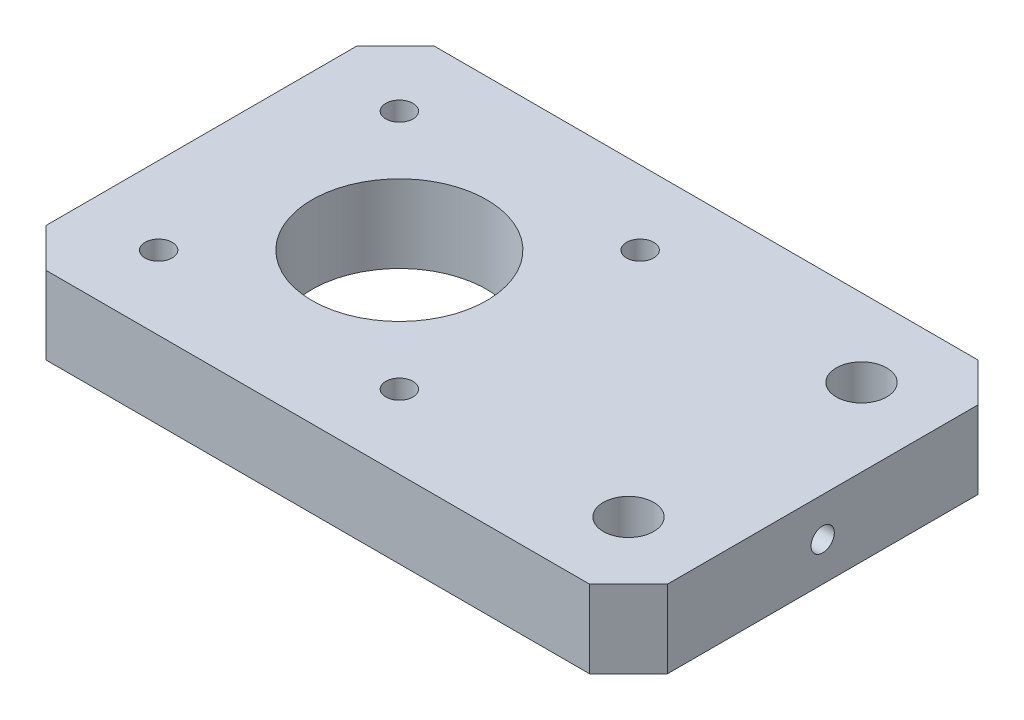
SolidWorks part; units mm, degrees
material "ABS PC"
ref_plane "Спереди" through (0, 0, 0) normal (0, 0, 1) x (1, 0, 0)
ref_plane "Сверху" through (0, 0, 0) normal (0, 1, 0) x (1, 0, 0)
ref_plane "Справа" through (0, 0, 0) normal (1, 0, 0) x (0, 0, -1)
sketch "Sketch1" plane through (0, 0, 0) normal (0, 1, 0) x (1, 0, 0)
  line L0 (10, 15.5) -> (10, -15.5) construction
  line L1 (0, 25) -> (80, 25)
  line L2 (0, 25) -> (0, -25)
  line L3 (0, -25) -> (80, -25)
  line L4 (80, 25) -> (80, -25)
  line L5 (70, 15) -> (70, -15) construction
  circle A0 centre (10, 15.5) radius 1.75
  circle A1 centre (10, -15.5) radius 1.75
  circle A2 centre (25.5, 0) radius 11.25
  circle A3 centre (41, 15.5) radius 1.75
  circle A4 centre (41, -15.5) radius 1.75
  circle A5 centre (70, 15) radius 3.25
  circle A6 centre (70, -15) radius 3.25
  point P19 (10, 0)
  point P21 (70, 0)
  dimension "D1" = 3.5
  dimension "D2" = 6.5
  dimension "D3" = 31
  dimension "D4" = 31
  dimension "D5" = 22.5
  dimension "D7" = 30
  dimension "D9" = 10
  dimension "D11" = 15.5
  dimension "D6" = 50
  dimension "D8" = 80
  dimension "D10" = 10
extrude "Boss-Extrude1" add sketch "Sketch1" along normal blind 10
sketch "Sketch2" plane through (80, 0, 0) normal (1, 0, 0) x (0, 0, -1)
  line L0 (-25, 0) -> (25, 0) construction
  circle A0 centre (0, 5) radius 1.5
  dimension "D1" = 5
  dimension "D2" = 3
extrude "Cut-Extrude1" cut sketch "Sketch2" against normal blind 15
chamfer "Chamfer1" distance 5 angle 45 4 edges at (0, 5, 25) (0, 5, -25) (80, 5, -25) (80, 5, 25)
